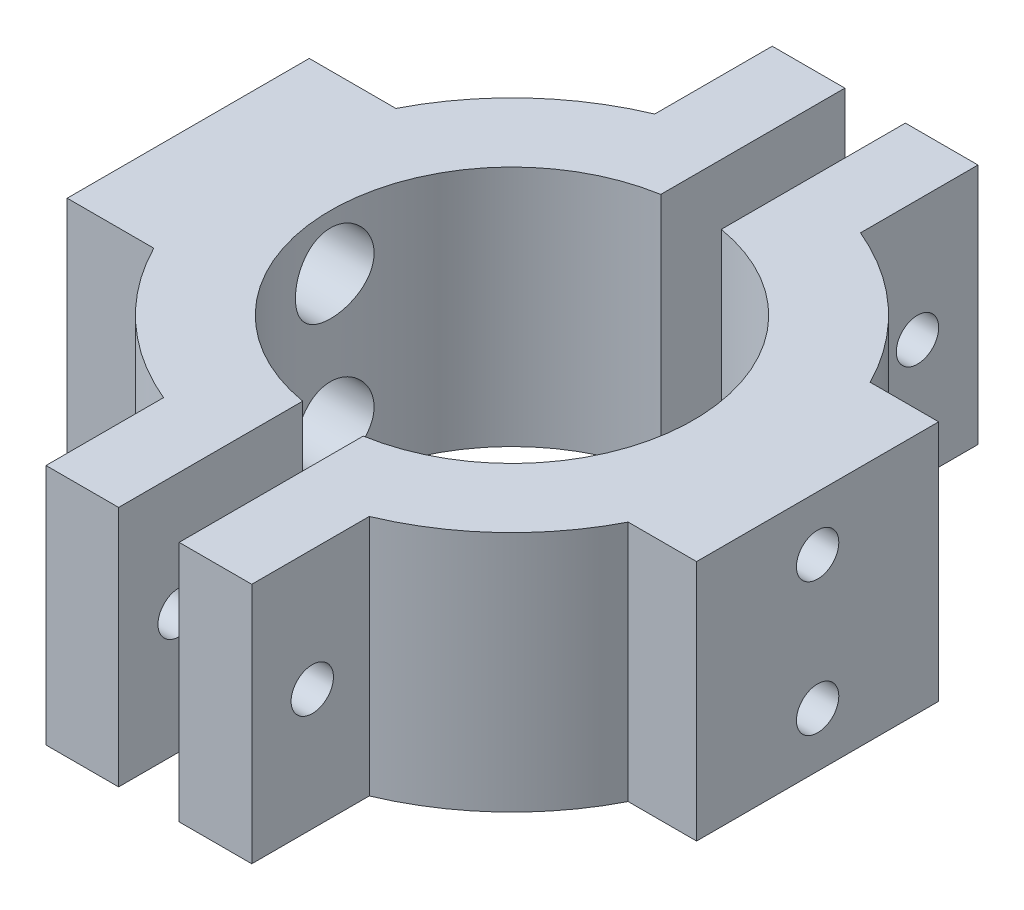
SolidWorks part; units mm, degrees
material "ABS"
ref_plane "前视基准面" through (0, 0, 0) normal (0, 0, 1) x (1, 0, 0)
ref_plane "上视基准面" through (0, 0, 0) normal (0, 1, 0) x (1, 0, 0)
ref_plane "右视基准面" through (0, 0, 0) normal (1, 0, 0) x (0, 0, -1)
other "Configuration Table"
sketch "草图1" plane through (0, 0, 0) normal (0, 1, 0) x (1, 0, 0)
  line L0 (-26.75, 10) -> (-19.5959, 10)
  line L2 (-2.5, 30) -> (-2.5, 14.7902)
  line L4 (2.5, 30) -> (2.5, 14.7902)
  line L10 (-26.75, 10) -> (-26.75, -10)
  line L12 (25.25, 10) -> (25.25, -10)
  line L13 (-26.75, -10) -> (-19.5959, -10)
  line L14 (0, 0) -> (29.9849, 0) construction
  line L15 (2.5, 30) -> (8.5, 30)
  line L16 (8.5, 30) -> (8.5, 20.2916)
  line L17 (-2.5, 30) -> (-8.5, 30)
  line L18 (-8.5, 30) -> (-8.5, 20.2916)
  line L19 (-2.5, -30) -> (-8.5, -30)
  line L20 (-8.5, -30) -> (-8.5, -20.2916)
  line L21 (2.5, -30) -> (8.5, -30)
  line L22 (8.5, -30) -> (8.5, -20.2916)
  line L24 (19.5959, 10) -> (25.25, 10)
  line L25 (19.5959, -10) -> (25.25, -10)
  line L27 (2.5, -14.7902) -> (2.5, -30)
  line L28 (-2.5, -14.7902) -> (-2.5, -30)
  arc A0 (-2.5, 14.7902) -> (-2.5, -14.7902) centre (0, 0) ccw
  arc A1 (-8.5, 20.2916) -> (-19.5959, 10) centre (0, 0) ccw
  arc A2 (2.5, -14.7902) -> (2.5, 14.7902) centre (0, 0) ccw
  arc A3 (8.5, -20.2916) -> (19.5959, -10) centre (0, 0) ccw
  arc A4 (-19.5959, -10) -> (-8.5, -20.2916) centre (0, 0) ccw
  arc A5 (19.5959, 10) -> (8.5, 20.2916) centre (0, 0) ccw
  dimension "D1" = 30
  dimension "D6" = 7
  dimension "D2" = 5
  dimension "D3" = 60
  dimension "D4" = 25.25
  dimension "D5" = 26.75
  dimension "D7" = 20
  dimension "D10" = 6
  dimension "D11" = 2.5
extrude "凸台-拉伸1" add sketch "草图1" along normal mid plane 20
sketch "草图3" plane through (25.25, 0, 0) normal (1, 0, 0) x (0, 0, -1)
  line L0 (0, -5.5) -> (0, 5.5) construction
  circle A0 centre (0, 5.5) radius 1.75
  circle A1 centre (0, -5.5) radius 1.75
  point P4 (0, 0)
  dimension "D2" = 3.5
  dimension "D1" = 11
extrude "切除-拉伸1" cut sketch "草图3" against normal blind 100
sketch "草图4" plane through (0, 0, 0) normal (1, 0, 0) x (0, 0, -1)
  circle A0 centre (0, 5.5) radius 3.25
  circle A1 centre (0, -5.5) radius 3.25
  dimension "D1" = 6.5
extrude "切除-拉伸2" cut sketch "草图4" against normal mid plane 40
sketch "草图5" plane through (-8.5, 0, 0) normal (-1, 0, 0) x (0, 0, 1)
  line L1 (30, 10) -> (30, -10) construction
  line L3 (-30, 10) -> (-30, -10) construction
  circle A0 centre (-25, 0) radius 1.75
  circle A1 centre (25, 0) radius 1.75
  dimension "D1" = 3.5
  dimension "D2" = 5
  dimension "D3" = 5
extrude "切除-拉伸3" cut sketch "草图5" against normal blind 40
sketch "草图6" plane through (-26.75, 0, 0) normal (-1, 0, 0) x (0, 0, 1)
  line L0 (-5, 0) -> (5, 0) construction
  line L1 (-5, 1.5) -> (5, 1.5)
  line L2 (-5, -1.5) -> (5, -1.5)
  arc A0 (-5, 1.5) -> (-5, -1.5) centre (-5, 0) ccw
  arc A1 (5, -1.5) -> (5, 1.5) centre (5, 0) ccw
  point P2 (0, 0)
  dimension "D2" = 1.5
  dimension "D1" = 10
extrude "切除-拉伸4" cut sketch "草图6" against normal blind 1
